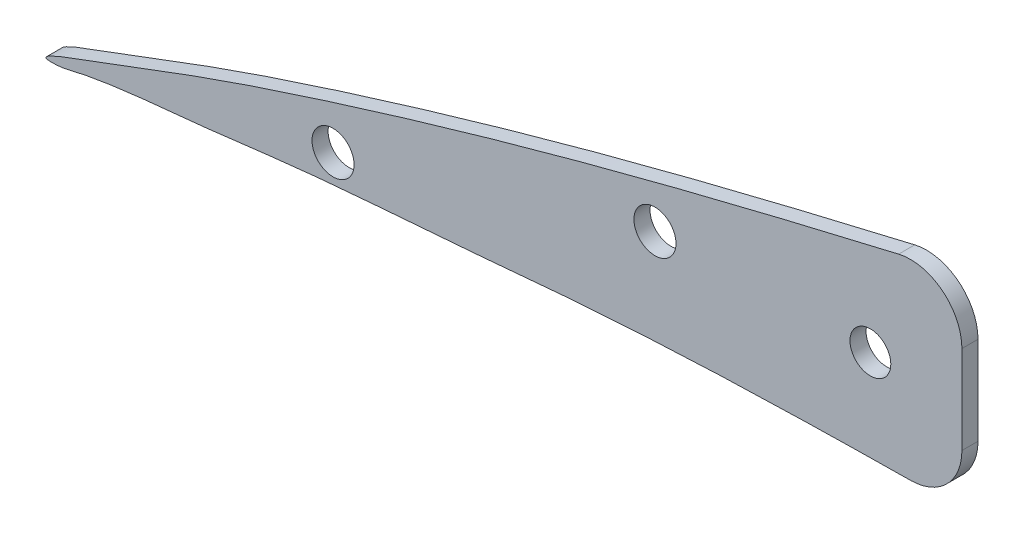
SolidWorks part; units mm, degrees
material "Balsa"
ref_plane "Front Plane" through (0, 0, 0) normal (0, 0, 1) x (1, 0, 0)
ref_plane "Top Plane" through (0, 0, 0) normal (0, 1, 0) x (1, 0, 0)
ref_plane "Right Plane" through (0, 0, 0) normal (1, 0, 0) x (0, 0, -1)
sketch "Sketch1" plane through (0, 0, 0) normal (0, 0, 1) x (1, 0, 0)
  line L0 (99.3264, 18.4044) -> (99.3264, -2.9864)
  line L1 (73.9264, 12.4163) -> (99.3264, -2.9864) construction
  line L8 (238.3754, -9.6537) -> (238.3754, -27.8289) construction
  line L9 (73.9264, -3.3744) -> (73.9264, 12.4163) construction
  line L10 (238.3754, -9.6537) -> (3.4483, -9.6537) construction
  line L11 (73.9264, -3.3744) -> (73.9264, 12.4163) construction
  line L12 (99.3264, 18.4044) -> (73.9264, -3.3744) construction
  spline S0 degree 3 poles (5.0476, -9.6537) (1.3045, -10.0425) (11.5033, -6.3535) (19.7236, -3.0928) (52.9152, 7.6459) (77.8898, 13.46) (99.3264, 18.4044) knots 0 0 0 0 0.059915 0.175786 0.369275 1 1 1 1
  spline S1 degree 3 poles (5.0476, -9.6537) (9.4826, -8.5461) (16.9885, -8.0769) (30.3366, -6.2544) (41.9467, -5.566) (65.8658, -3.2313) (83.9748, -3.0891) (99.3264, -2.9864) knots 0 0 0 0 0.144322 0.237948 0.427123 0.512832 1 1 1 1
  spline S6 degree 3 poles (5.0476, -9.6537) (9.4826, -8.5461) (16.9885, -8.0769) (30.3366, -6.2543) (41.9468, -5.5667) (60.7635, -3.7271) (83.9252, -2.9983) (119.6066, -2.8533) (155.1663, -4.9989) (188.2936, -10.0956) (210.9238, -14.2463) (226.8417, -14.3145) (237.449, -14.868) (238.3754, -9.6537) knots 0 0 0 0 0.057787 0.095275 0.171021 0.205339 0.335319 0.464904 0.658702 0.785512 0.893517 0.943092 1 1 1 1 construction
  spline S7 degree 3 poles (238.3754, -9.6537) (237.7653, -4.112) (231.8626, 3.793) (218.5807, 12.9188) (199.1338, 22.0262) (170.9048, 27.4643) (139.4251, 26.4056) (107.9057, 20.4989) (74.2413, 12.6461) (44.8793, 5.0523) (19.7218, -3.094) (11.5035, -6.3533) (1.3045, -10.0425) (5.0476, -9.6537) knots 0 0 0 0 0.060864 0.113688 0.188609 0.312909 0.448482 0.557612 0.691544 0.852438 0.929756 0.976058 1 1 1 1 construction
  dimension "D1" = 25.4
  dimension "D3" = 164.449
  dimension "D4" = 234.9271
extrude "Boss-Extrude1" add sketch "Sketch1" along normal blind 226.06
sketch "Sketch2" plane through (0, 0, 0) normal (0, 1, 0) x (1, 0, 0)
  line L0 (169.6815, 0) -> (169.6815, -226.06)
  line L1 (169.6815, -226.06) -> (73.1644, -226.06)
  line L2 (73.1644, -226.06) -> (73.1644, -197.485)
  line L3 (73.1644, -197.485) -> (93.7384, -197.485)
  line L4 (93.7384, -197.485) -> (93.7384, -28.575)
  line L5 (93.7384, -28.575) -> (73.1644, -28.575)
  line L6 (73.1644, -28.575) -> (73.1644, 0)
  line L7 (73.1644, 0) -> (169.6815, 0)
  line L8 (3.4109, -226.06) -> (99.3264, -226.06) construction
  line L9 (99.3264, 0) -> (3.4109, 0) construction
  line L10 (99.3264, -226.06) -> (99.3264, 0) construction
  dimension "D1" = 20.574
  dimension "D2" = 5.588
  dimension "D3" = 75.9431
  dimension "D4" = 28.575
  dimension "D5" = 0
  dimension "D6" = 0
extrude "Cut-Extrude1" cut sketch "Sketch2" against normal through all both and the other way through all
fillet "Fillet1" radius 5.08 6 edges at (73.1644, -3.3889, 14.2875) (73.1644, 12.236, 14.2875) (93.7384, -3.0267, 113.03) (93.7384, 17.1136, 113.03) (73.1644, -3.3889, 211.7725) (73.1644, 12.236, 211.7725)
sketch "Sketch4" plane through (0, 0, 0) normal (1, 0, 0) x (0, 0, -1)
  line L0 (-197.485, 2.0054) -> (-197.485, 10.7162) construction
  line L1 (-238.6023, -25.5438) -> (-197.485, -25.5438)
  line L2 (-238.6023, -25.5438) -> (-238.6023, 42.1009)
  line L3 (-238.6023, 42.1009) -> (-197.485, 42.1009)
  line L4 (-197.485, -25.5438) -> (-197.485, 42.1009)
  line L6 (-195.8975, 42.1009) -> (15.385, 42.1009)
  line L7 (-195.8975, 42.1009) -> (-195.8975, -39.6297)
  line L8 (-195.8975, -39.6297) -> (15.385, -39.6297)
  line L9 (15.385, 42.1009) -> (15.385, -39.6297)
  dimension "D1" = 1.5875
extrude "Cut-Extrude5" cut sketch "Sketch4" along normal through all
sketch "Sketch3" plane through (0, 0, 0) normal (0, 0, 1) x (1, 0, 0)
  line L8 (238.3754, -9.6537) -> (238.3754, -27.8289) construction
  circle A0 centre (84.7136, 5.8749) radius 2.013
  dimension "D1" = 4.0259
extrude "Cut-Extrude2" cut sketch "Sketch3" along normal through all
sketch "Sketch5" plane through (0, 0, 197.485) normal (0, 0, 1) x (1, 0, 0)
  circle A2 centre (31.7176, -3.5577) radius 2.075
  circle A3 centre (63.4676, 5.5863) radius 2.075
  dimension "D1" = 4.15
  dimension "D2" = 26.67
  dimension "D3" = 58.42
  dimension "D4" = 6.096
  dimension "D5" = 15.24
extrude "Cut-Extrude6" cut sketch "Sketch5" against normal through all
